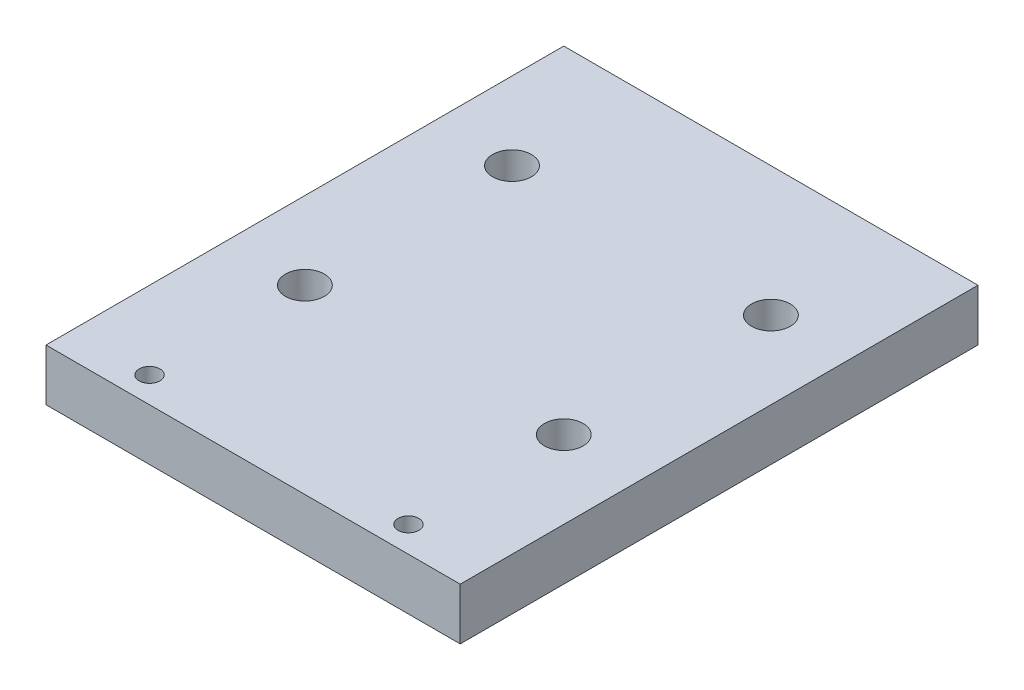
SolidWorks part; units mm, degrees
ref_plane "Front Plane" through (0, 0, 0) normal (0, 0, 1) x (1, 0, 0)
ref_plane "Top Plane" through (0, 0, 0) normal (0, 1, 0) x (1, 0, 0)
ref_plane "Right Plane" through (0, 0, 0) normal (1, 0, 0) x (0, 0, -1)
sketch "Sketch1" plane through (0, 0, 0) normal (0, 1, 0) x (1, 0, 0)
  line L1 (-50.8, -63.5) -> (50.8, -63.5)
  line L2 (-50.8, -63.5) -> (-50.8, 63.5)
  line L3 (-50.8, 63.5) -> (50.8, 63.5)
  line L4 (50.8, -63.5) -> (50.8, 63.5)
  line L5 (-50.8, -63.5) -> (50.8, 63.5) construction
  line L6 (-50.8, 63.5) -> (50.8, -63.5) construction
  point P0 (0, 0)
  dimension "D1" = 101.6
  dimension "D2" = 127
extrude "Boss-Extrude1" add sketch "Sketch1" along normal blind 12.7 contours L3 L4 L1 L2
hole_wizard "CSK for #10 Flat Head Machine Screw (100)1" positions "Sketch3" profile "Sketch2" countersink size "#10" standard "ANSI Inch"
sketch "Sketch3" plane through (0, 0, 0) normal (0, -1, 0) x (-1, 0, 0)
  line L0 (50.8, -63.5) -> (50.8, 63.5) construction
  line L1 (-50.8, -63.5) -> (-50.8, 63.5) construction
  line L2 (50.8, -63.5) -> (-50.8, -63.5) construction
  point P0 (31.75, -57.15)
  point P2 (-31.75, -57.15)
  dimension "D1" = 19.05
  dimension "D2" = 19.05
  dimension "D3" = 6.35
  dimension "D4" = 6.35
sketch "Sketch2" plane through (-31.75, 0, 57.15) normal (1, 0, 0) x (0, 0, -1)
  line L0 (0, 0) -> (0, 14.2338)
  line L1 (0, 14.2338) -> (2.5527, 12.7)
  line L2 (2.5527, 12.7) -> (2.5527, 1.9608)
  line L3 (2.5527, 1.9608) -> (4.8895, 0)
  line L5 (4.8895, 0) -> (0, 0)
  line L6 (-2.5527, 1.9608) -> (-4.8895, 0) construction
  line L10 (0, 14.2338) -> (-2.5527, 12.7) construction
  line L11 (0, -6.35) -> (0, 107.95) construction
  dimension "Hole Dia." = 5.1054
  dimension "Hole Depth" = 12.7
  dimension "Near C'Sink Dia." = 9.779
  dimension "Near C'Sink Angle" = 100
  dimension "Drill Angle" = 118
hole_wizard "3/8 (0.375) Diameter Hole1" positions "Sketch6" profile "Sketch4" hole size "3/8" standard "ANSI Inch"
sketch "Sketch6" plane through (0, 12.7, 0) normal (0, 1, 0) x (1, 0, 0)
  line L0 (-50.8, -63.5) -> (-50.8, 63.5) construction
  line L1 (50.8, -63.5) -> (50.8, 63.5) construction
  line L3 (-50.8, -63.5) -> (50.8, -63.5) construction
  point P0 (-31.75, 31.75)
  point P2 (31.75, 31.75)
  point P4 (-31.75, -19.05)
  point P6 (31.75, -19.05)
  dimension "D1" = 19.05
  dimension "D2" = 19.05
  dimension "D3" = 19.05
  dimension "D4" = 19.05
  dimension "D5" = 44.45
  dimension "D6" = 44.45
  dimension "D7" = 50.8
  dimension "D8" = 50.8
sketch "Sketch4" plane through (-31.75, 12.7, -31.75) normal (1, 0, 0) x (0, 0, 1)
  line L0 (0, 0) -> (0, 28.2616)
  line L1 (0, 28.2616) -> (4.7625, 25.4)
  line L2 (4.7625, 25.4) -> (4.7625, 0)
  line L5 (4.7625, 0) -> (0, 0)
  line L10 (0, 28.2616) -> (-4.7625, 25.4) construction
  line L11 (0, -6.35) -> (0, 107.95) construction
  dimension "Hole Dia." = 9.525
  dimension "Hole Depth" = 25.4
  dimension "Drill Angle" = 118
